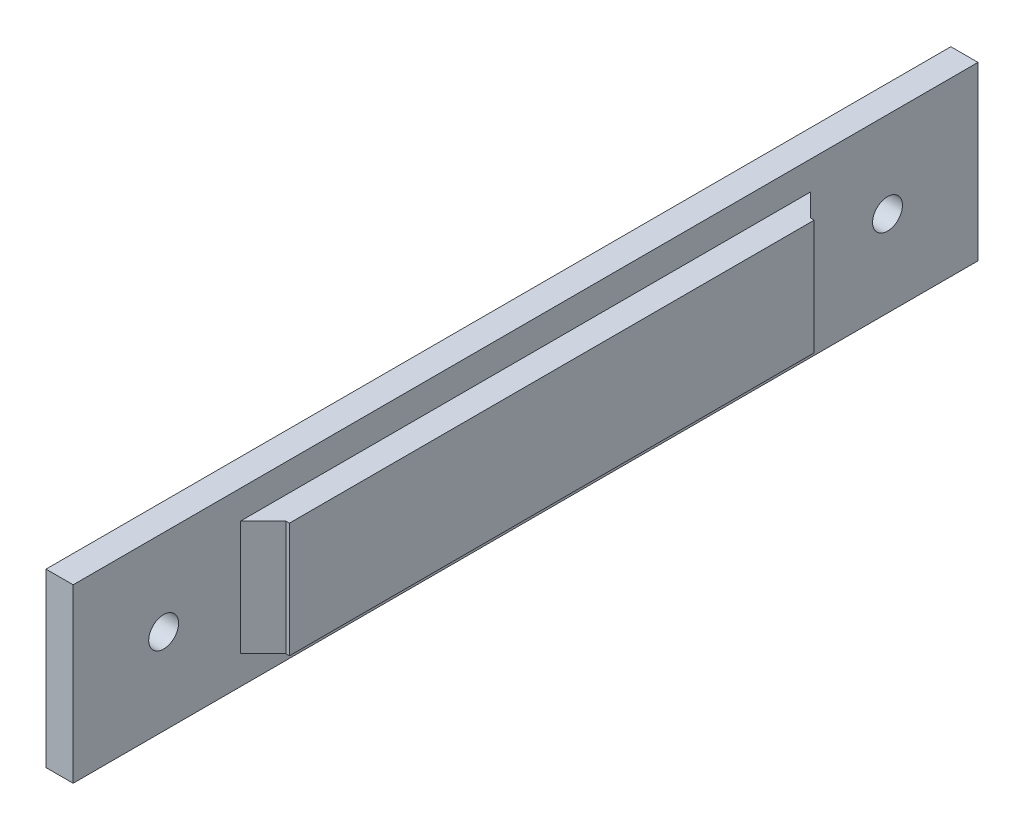
SolidWorks part; units mm, degrees
ref_plane "前视基准面" through (0, 0, 0) normal (0, 0, 1) x (1, 0, 0)
ref_plane "上视基准面" through (0, 0, 0) normal (0, 1, 0) x (1, 0, 0)
ref_plane "右视基准面" through (0, 0, 0) normal (1, 0, 0) x (0, 0, -1)
sketch "草图1" plane through (0, 0, 0) normal (0, 0, 1) x (1, 0, 0)
  line L1 (0, 0) -> (13, 0)
  line L2 (0, 0) -> (0, 13)
  line L3 (0, 13) -> (13, 13)
  line L4 (13, 0) -> (13, 13)
  dimension "D1" = 13
  dimension "D2" = 13
extrude "拉伸-薄壁1" add sketch "草图1" along normal blind 100 thin
sketch "草图2" plane through (-3, 0, 0) normal (-1, 0, 0) x (0, 0, 1)
  line L0 (0, 16) -> (0, -3) construction
  line L1 (100, 16) -> (100, -3) construction
  circle A0 centre (10, 6.5) radius 1.65
  circle A1 centre (90, 6.5) radius 1.65
  dimension "D1" = 3.3
  dimension "D2" = 3.3
  dimension "D3" = 10
  dimension "D4" = 10
extrude "切除-拉伸1" cut sketch "草图2" against normal blind 30
sketch "草图3" plane through (16, 0, 0) normal (1, 0, 0) x (0, 0, -1)
  line L1 (-100, 16) -> (0, 16)
  line L2 (-100, 16) -> (-100, -3)
  line L3 (-100, -3) -> (0, -3)
  line L4 (0, 16) -> (0, -3)
extrude "切除-拉伸2" cut sketch "草图3" against normal blind 16
sketch "草图4" plane through (0, 0, 0) normal (1, 0, 0) x (0, 0, -1)
  line L0 (0, 16) -> (0, -3) construction
  line L1 (-79, 12.85) -> (-21, 12.85)
  line L2 (-79, 12.85) -> (-79, 0.15)
  line L3 (-79, 0.15) -> (-21, 0.15)
  line L4 (-21, 12.85) -> (-21, 0.15)
  line L5 (-100, 16) -> (-100, -3) construction
  line L6 (-100, -3) -> (0, -3) construction
  line L7 (0, 16) -> (-100, 16) construction
  point P8 (-21, 6.5)
  dimension "D1" = 21
  dimension "D2" = 21
  dimension "D3" = 12.7
  dimension "D4" = 9.5
  dimension "D5" = 3.15
  dimension "D6" = 3.15
extrude "凸台-拉伸1" add sketch "草图4" along normal blind 2.9
chamfer "倒角1" distance 2.5 angle 45 2 edges at (0, 6.5, 21) (0, 6.5, 79)
sketch "草图5" plane through (-3, 0, 0) normal (-1, 0, 0) x (0, 0, 1)
  text T0 "L3"
extrude "切除-拉伸3" cut sketch "草图5" against normal blind 0.5
